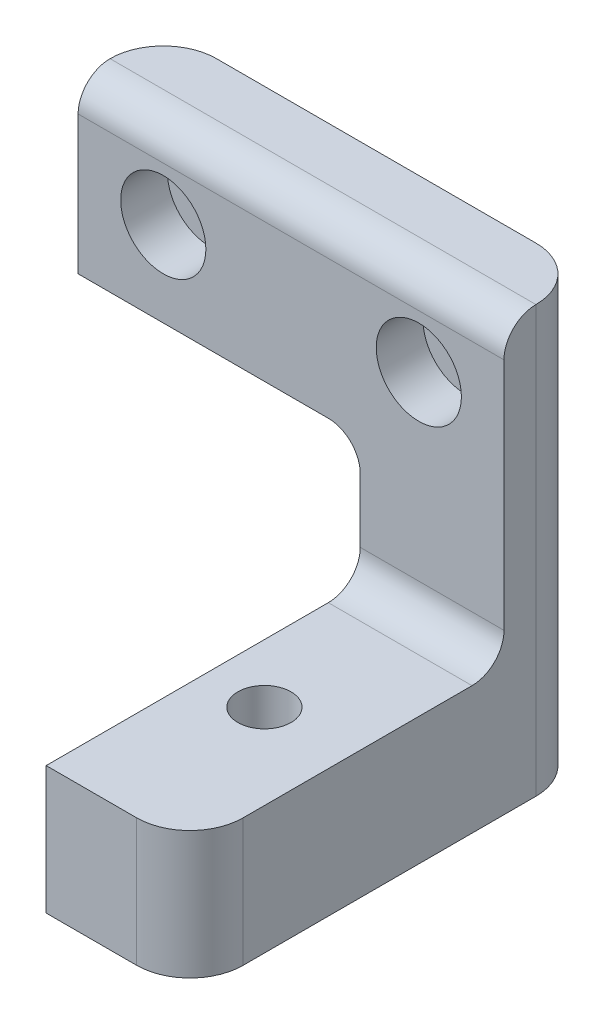
SolidWorks part; units mm, degrees
material "K110"
ref_plane "Front Plane" through (0, 0, 0) normal (0, 0, 1) x (1, 0, 0)
ref_plane "Top Plane" through (0, 0, 0) normal (0, 1, 0) x (1, 0, 0)
ref_plane "Right Plane" through (0, 0, 0) normal (1, 0, 0) x (0, 0, -1)
sketch "Sketch1" plane through (0, 0, 0) normal (0, 1, 0) x (1, 0, 0)
  line L1 (-20, -18.75) -> (20, -18.75)
  line L2 (-20, -18.75) -> (-20, 18.75)
  line L3 (-20, 18.75) -> (20, 18.75)
  line L4 (20, -18.75) -> (20, 18.75)
  line L5 (-20, -18.75) -> (20, 18.75) construction
  line L6 (-20, 18.75) -> (20, -18.75) construction
  point P0 (0, 0)
  dimension "D1" = 37.5
  dimension "D2" = 40
extrude "Boss-Extrude1" add sketch "Sketch1" against normal blind 40
sketch "Sketch2" plane through (20, 0, 0) normal (1, 0, 0) x (0, 0, -1)
  line L0 (18.75, -40) -> (18.75, 0) construction
  line L1 (-18.75, 0) -> (10.75, 0)
  line L2 (-18.75, 0) -> (-18.75, -28)
  line L3 (-18.75, -28) -> (10.75, -28)
  line L4 (10.75, 0) -> (10.75, -28)
  dimension "D1" = 8
  dimension "D2" = 28
extrude "Cut-Extrude1" cut sketch "Sketch2" against normal up to next
fillet "Fillet1" radius 3 2 edges at (0, 0, -10.75) (0, -28, -10.75)
hole_wizard "M6 Tapped Hole1" positions "Sketch14" profile "Sketch4" tap size "M6" standard "ISO" end condition through all
sketch "Sketch14" plane through (0, -40, 0) normal (0, -1, 0) x (-1, 0, 0)
  line L0 (-20, -18.75) -> (-20, 18.75) construction
  line L2 (20, -18.75) -> (-20, -18.75) construction
  point P0 (-12, -3.75)
  dimension "D1" = 8
  dimension "D2" = 15
cosmetic thread "Hole Thread2"
sketch "Sketch4" plane through (12, -40, 3.75) normal (1, 0, 0) x (0, 0, -1)
  line L0 (0, 0) -> (0, 40)
  line L1 (0, 40) -> (2.5, 40)
  line L2 (2.5, 40) -> (2.5, 0.525)
  line L3 (2.5, 0.525) -> (3.025, 0)
  line L5 (3.025, 0) -> (0, 0)
  line L6 (-2.5, 0.525) -> (-3.025, 0) construction
  line L11 (0, -6.35) -> (0, 107.95) construction
  dimension "Thru Tap Drill Dia." = 5
  dimension "Thru Tap Drill Depth" = 40
  dimension "Near C'Sink Dia." = 6.05
  dimension "Near C'Sink Angle" = 90
fillet "Fillet2" radius 5 4 edges at (20, -20, -18.75) (20, -34, 18.75) (-20, -34, 18.75) (-20, -20, -18.75)
sketch "Sketch7" plane through (0, 0, 0) normal (0, 1, 0) x (1, 0, 0)
  line L0 (-15, -18.75) -> (15, -18.75) construction
  line L1 (-6.5, -18.75) -> (6.5, -18.75)
  line L2 (-6.5, -18.75) -> (-6.5, 10.75)
  line L3 (-6.5, 10.75) -> (6.5, 10.75)
  line L4 (6.5, -18.75) -> (6.5, 10.75)
  line L6 (0, 7.75) -> (0, -18.75) construction
  line L7 (-20, 13.75) -> (20, 13.75) construction
  dimension "D1" = 3
  dimension "13" = 13
extrude "Cut-Extrude2" cut sketch "Sketch7" against normal up to next
sketch "Sketch8" plane through (0, 0, 0) normal (1, 0, 0) x (0, 0, -1)
  line L1 (-18.75, -40) -> (10.75, -40)
  line L2 (-18.75, -40) -> (-18.75, -3)
  line L3 (-18.75, -3) -> (10.75, -3)
  line L4 (10.75, -40) -> (10.75, -3)
extrude "Cut-Extrude3" cut sketch "Sketch8" against normal up to next
sketch "Sketch9" plane through (-20, 0, 0) normal (-1, 0, 0) x (0, 0, 1)
  line L0 (-10.75, -40) -> (-10.75, -3) construction
  line L1 (-18.75, -40) -> (-10.75, -40)
  line L2 (-18.75, -40) -> (-18.75, -16.0022)
  line L3 (-18.75, -16.0022) -> (-10.75, -16.0022)
  line L4 (-10.75, -40) -> (-10.75, -16.0022)
  line L5 (-23.7522, -28.0022) -> (-13.75, -28.0022) construction
  dimension "D1" = 12
extrude "Cut-Extrude4" cut sketch "Sketch9" against normal up to surface (26.5 mm away) up to face at (6.5, -32.3243, 1.5257)
fillet "Fillet5" radius 3 1 edges at (6.5, -16.0022, -14.75)
hole_wizard "CBORE for M4 Hex Socket Head Cap Screw1" positions "Sketch12" profile "Sketch11" counterbore size "M4" standard "ISO" end condition through all
sketch "Sketch12" plane through (0, 0, -10.75) normal (0, 0, 1) x (1, 0, 0)
  line L0 (0, 0) -> (0, -16.0022) construction
  line L1 (3.5, -16.0022) -> (-20, -16.0022) construction
  line L3 (0, -8.0011) -> (-20, -8.0011) construction
  line L4 (-20, -16.0022) -> (-20, -3) construction
  line L6 (20, -25) -> (20, -3) construction
  point P1 (-12, -8.0011)
  point P3 (12, -8.0011)
  point P19 (0, 0)
  point P22 (0, 0)
  dimension "D1" = 8
  dimension "D2" = 8
sketch "Sketch11" plane through (-12, -8.0011, -10.75) normal (1, 0, 0) x (0, -1, 0)
  line L0 (0, 0) -> (0, 8)
  line L1 (0, 8) -> (2.15, 8)
  line L3 (2.15, 8) -> (2.15, 4.4)
  line L4 (2.15, 4.4) -> (4, 4.4)
  line L5 (4, 4.4) -> (4, 0)
  line L7 (4, 0) -> (0, 0)
  line L11 (0, -6.35) -> (0, 107.95) construction
  dimension "Thru Hole Dia." = 4.3
  dimension "Thru Hole Depth" = 8
  dimension "C'Bore Dia." = 8
  dimension "C'Bore Depth" = 4.4
